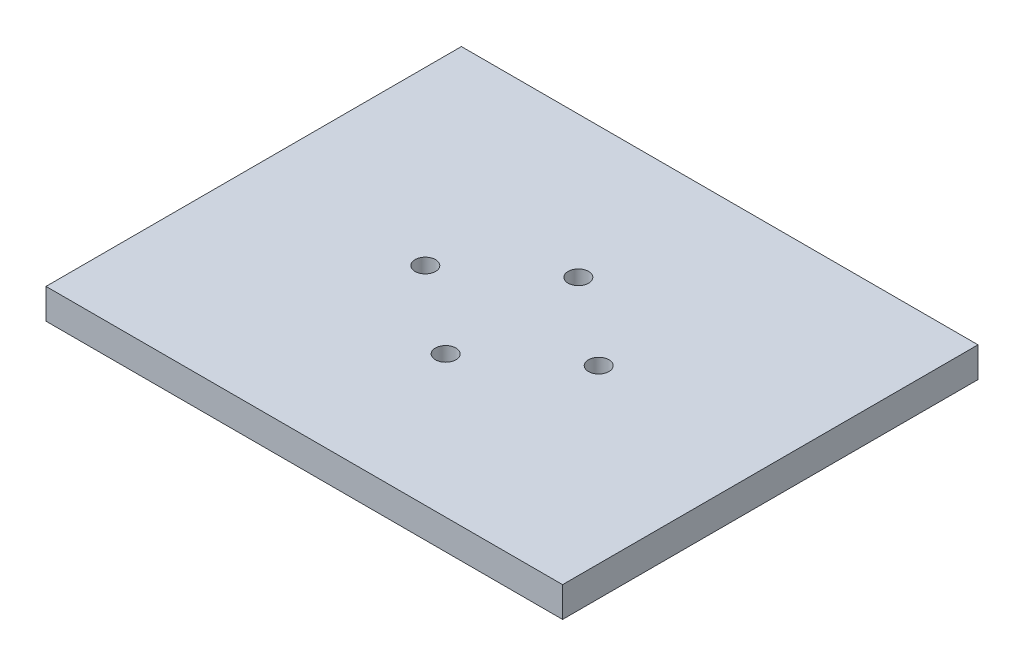
SolidWorks part; units mm, degrees
material "1060 Alloy"
ref_plane "Front Plane" through (0, 0, 0) normal (0, 0, 1) x (1, 0, 0)
ref_plane "Top Plane" through (0, 0, 0) normal (0, 1, 0) x (1, 0, 0)
ref_plane "Right Plane" through (0, 0, 0) normal (1, 0, 0) x (0, 0, -1)
sketch "Sketch1" plane through (0, 0, 0) normal (0, 1, 0) x (1, 0, 0)
  line L1 (57.825, 46.5) -> (-57.825, 46.5) construction
  line L2 (57.825, 46.5) -> (57.825, -46.5) construction
  line L3 (57.825, -46.5) -> (-57.825, -46.5) construction
  line L4 (-57.825, 46.5) -> (-57.825, -46.5) construction
  line L5 (-57.825, 46.5) -> (57.825, -46.5) construction
  line L6 (-57.825, 26.7384) -> (-42.825, 26.7384) construction
  line L36 (-42.825, 26.7384) -> (-9.5745, 0) construction
  line L37 (-9.5745, 0) -> (-42.825, -26.7384) construction
  line L38 (-42.825, -26.7384) -> (-57.825, -26.7384) construction
  line L39 (-57.825, -26.7384) -> (-57.825, -46.5) construction
  line L40 (-57.825, -46.5) -> (-33.2505, -46.5) construction
  line L41 (-33.2505, -46.5) -> (-33.2505, -34.4377) construction
  line L42 (-33.2505, -34.4377) -> (0, -7.6993) construction
  line L43 (0, -7.6993) -> (33.2505, -34.4377) construction
  line L44 (33.2505, -34.4377) -> (33.2505, -46.5) construction
  line L45 (33.2505, -46.5) -> (57.825, -46.5) construction
  line L46 (57.825, -46.5) -> (57.825, -26.7384) construction
  line L47 (57.825, -26.7384) -> (42.825, -26.7384) construction
  line L48 (42.825, -26.7384) -> (9.5745, 0) construction
  line L49 (9.5745, 0) -> (42.825, 26.7384) construction
  line L50 (42.825, 26.7384) -> (57.825, 26.7384) construction
  line L51 (57.825, 26.7384) -> (57.825, 46.5) construction
  line L52 (57.825, 46.5) -> (33.2505, 46.5) construction
  line L53 (33.2505, 46.5) -> (33.2505, 34.4377) construction
  line L54 (33.2505, 34.4377) -> (0, 7.6993) construction
  line L55 (0, 7.6993) -> (-33.2505, 34.4377) construction
  line L56 (-33.2505, 34.4377) -> (-33.2505, 46.5) construction
  line L57 (-33.2505, 46.5) -> (-57.825, 46.5) construction
  line L58 (-57.825, 46.5) -> (-57.825, 26.7384) construction
  line L59 (-57.825, -46.5) -> (57.825, 46.5) construction
  line L64 (42.825, 26.7384) -> (42.825, 34.4377)
  line L65 (42.825, 26.7384) -> (33.2505, 34.4377) construction
  line L66 (42.825, 34.4377) -> (33.2505, 34.4377)
  line L67 (33.2505, 34.4377) -> (-33.2505, 34.4377)
  line L68 (-33.2505, 34.4377) -> (-42.825, 34.4377)
  line L69 (-42.825, 34.4377) -> (-42.825, 26.7384)
  line L70 (-42.825, 26.7384) -> (-42.825, -26.7384)
  line L71 (-42.825, -26.7384) -> (-42.825, -34.4377)
  line L72 (-42.825, -34.4377) -> (-33.2505, -34.4377)
  line L73 (-33.2505, -34.4377) -> (33.2505, -34.4377)
  line L74 (33.2505, -34.4377) -> (42.825, -34.4377)
  line L75 (42.825, -34.4377) -> (42.825, -26.7384)
  line L78 (42.825, -26.7384) -> (42.825, 26.7384)
  line L79 (-9.5745, 0) -> (9.5745, 0) construction
  line L80 (0, 7.6993) -> (0, -7.6993) construction
  circle A1 centre (0, 11) radius 1.7
  circle A3 centre (-14.375, 0) radius 1.7
  circle A4 centre (0, -11) radius 1.7
  circle A5 centre (14.375, 0) radius 1.7
  dimension "D6" = 3.4
  dimension "D8" = 3.4
  dimension "D1" = 115.65
  dimension "D2" = 93
  dimension "D3" = 12
  dimension "D4" = 15
  dimension "D5" = 28.75
  dimension "D7" = 22
extrude "Boss-Extrude1" add sketch "Sketch1" along normal blind 5
equation "\"L1L\"=500"
equation "\"L1Thick\"=6.35"
equation "\"Harm-Drive-Outer\"=74.5"
equation "\"L1-Spacing\"=115.65"
equation "\"L-Bracket-HoleToWall\"=12.5"
equation "\"L-Bracket-HoleToSide\"=11"
equation "\"Bracket-Hole-D\"=6.8"
equation "\"D1@Sketch1\"=\"L1-Spacing\""
